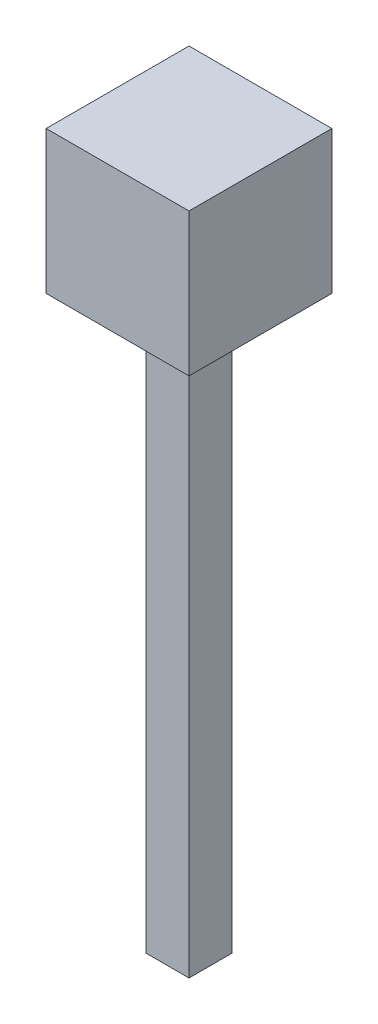
SolidWorks part; units mm, degrees
ref_plane "Front Plane" through (0, 0, 0) normal (0, 0, 1) x (1, 0, 0)
ref_plane "Top Plane" through (0, 0, 0) normal (0, 1, 0) x (1, 0, 0)
ref_plane "Right Plane" through (0, 0, 0) normal (1, 0, 0) x (0, 0, -1)
sketch "Sketch1" plane through (0, 0, 0) normal (0, 1, 0) x (1, 0, 0)
  line L1 (-6, 6) -> (6, 6)
  line L2 (-6, 6) -> (-6, -6)
  line L3 (-6, -6) -> (6, -6)
  line L4 (6, 6) -> (6, -6)
  line L5 (-6, 6) -> (6, -6) construction
  line L6 (-6, -6) -> (6, 6) construction
  line L7 (-3, 3) -> (3, 3)
  line L8 (-3, 3) -> (-3, -3)
  line L9 (-3, -3) -> (3, -3)
  line L10 (3, 3) -> (3, -3)
  line L11 (-3, 3) -> (3, -3) construction
  line L12 (-3, -3) -> (3, 3) construction
  point P0 (0, 0)
  point P6 (0, 0)
  dimension "D1" = 12
  dimension "D2" = 12
  dimension "D3" = 6
extrude "Boss-Extrude1" add sketch "Sketch1" along normal blind 100 contours L10 L7 L8 L9
sketch "Sketch2" plane through (0, 100, 0) normal (0, 1, 0) x (1, 0, 0)
  line L1 (-10, 10) -> (10, 10)
  line L2 (-10, 10) -> (-10, -10)
  line L3 (-10, -10) -> (10, -10)
  line L4 (10, 10) -> (10, -10)
  line L5 (-10, 10) -> (10, -10) construction
  line L6 (-10, -10) -> (10, 10) construction
  point P0 (0, 0)
  dimension "D1" = 20
extrude "Boss-Extrude2" add sketch "Sketch2" against normal blind 20
